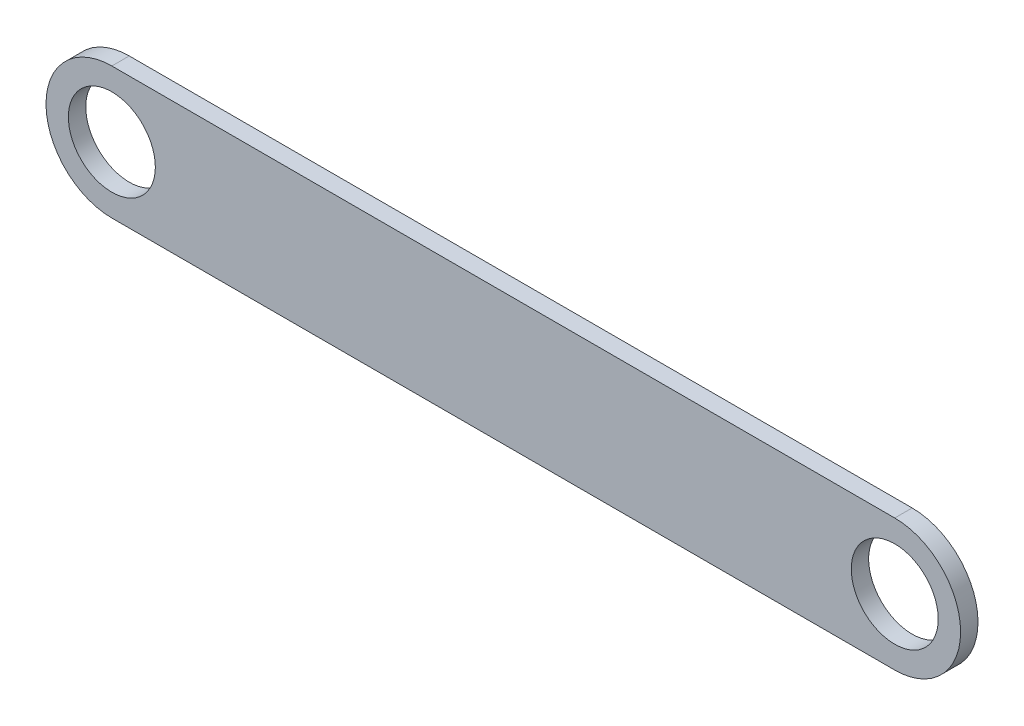
SolidWorks part; units mm, degrees
ref_plane "Front Plane" through (0, 0, 0) normal (0, 0, 1) x (1, 0, 0)
ref_plane "Top Plane" through (0, 0, 0) normal (0, 1, 0) x (1, 0, 0)
ref_plane "Right Plane" through (0, 0, 0) normal (1, 0, 0) x (0, 0, -1)
sketch "Sketch1" plane through (0, 0, 0) normal (0, 0, 1) x (1, 0, 0)
  line L0 (-225, 0) -> (225, 0) construction
  line L1 (-225, 37.8505) -> (225, 37.8505)
  line L2 (-225, -37.8505) -> (225, -37.8505)
  arc A0 (-225, 37.8505) -> (-225, -37.8505) centre (-225, 0) ccw
  arc A1 (225, -37.8505) -> (225, 37.8505) centre (225, 0) ccw
  point P2 (0, 0)
  dimension "D1" = 450
extrude "Boss-Extrude1" add sketch "Sketch1" along normal blind 10
sketch "Sketch2" plane through (0, 0, 10) normal (0, 0, 1) x (1, 0, 0)
  circle A0 centre (-225, 0) radius 25
  circle A1 centre (225, 0) radius 25
  dimension "D1" = 50
  dimension "D2" = 50
extrude "Cut-Extrude1" cut sketch "Sketch2" against normal blind 10
